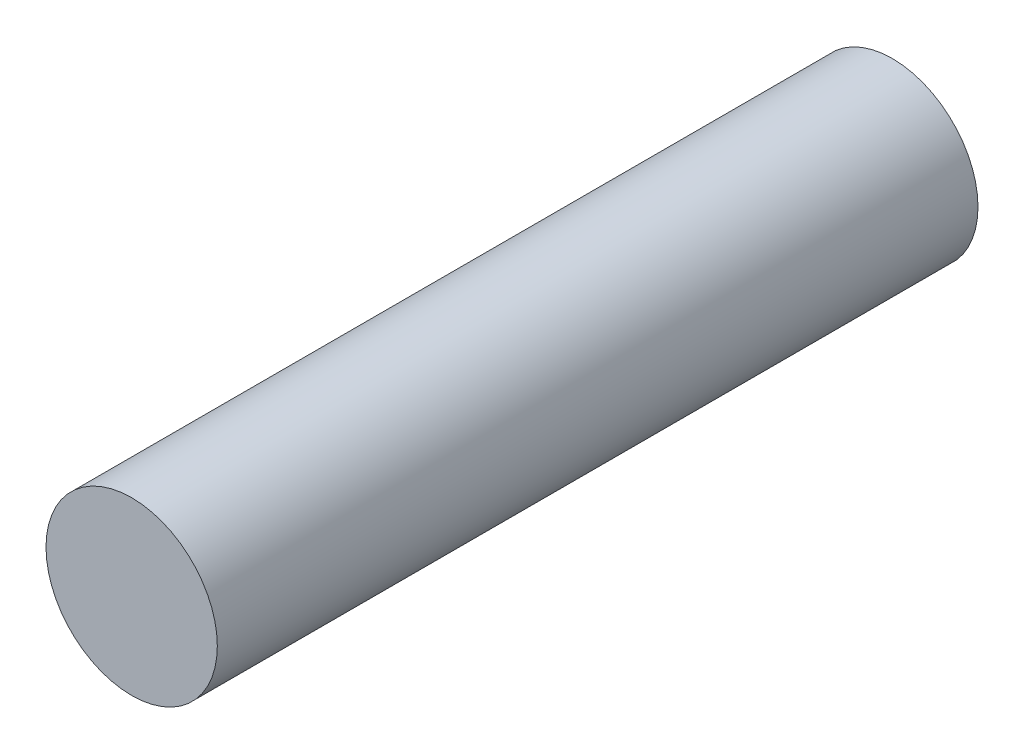
SolidWorks part; units mm, degrees
ref_plane "Front Plane" through (0, 0, 0) normal (0, 0, 1) x (1, 0, 0)
ref_plane "Top Plane" through (0, 0, 0) normal (0, 1, 0) x (1, 0, 0)
ref_plane "Right Plane" through (0, 0, 0) normal (1, 0, 0) x (0, 0, -1)
sketch "Sketch1" plane through (0, 0, 0) normal (0, 0, 1) x (1, 0, 0)
  circle A0 centre (0, 0) radius 12.5
  dimension "D1" = 25
extrude "Boss-Extrude1" add sketch "Sketch1" along normal blind 111
